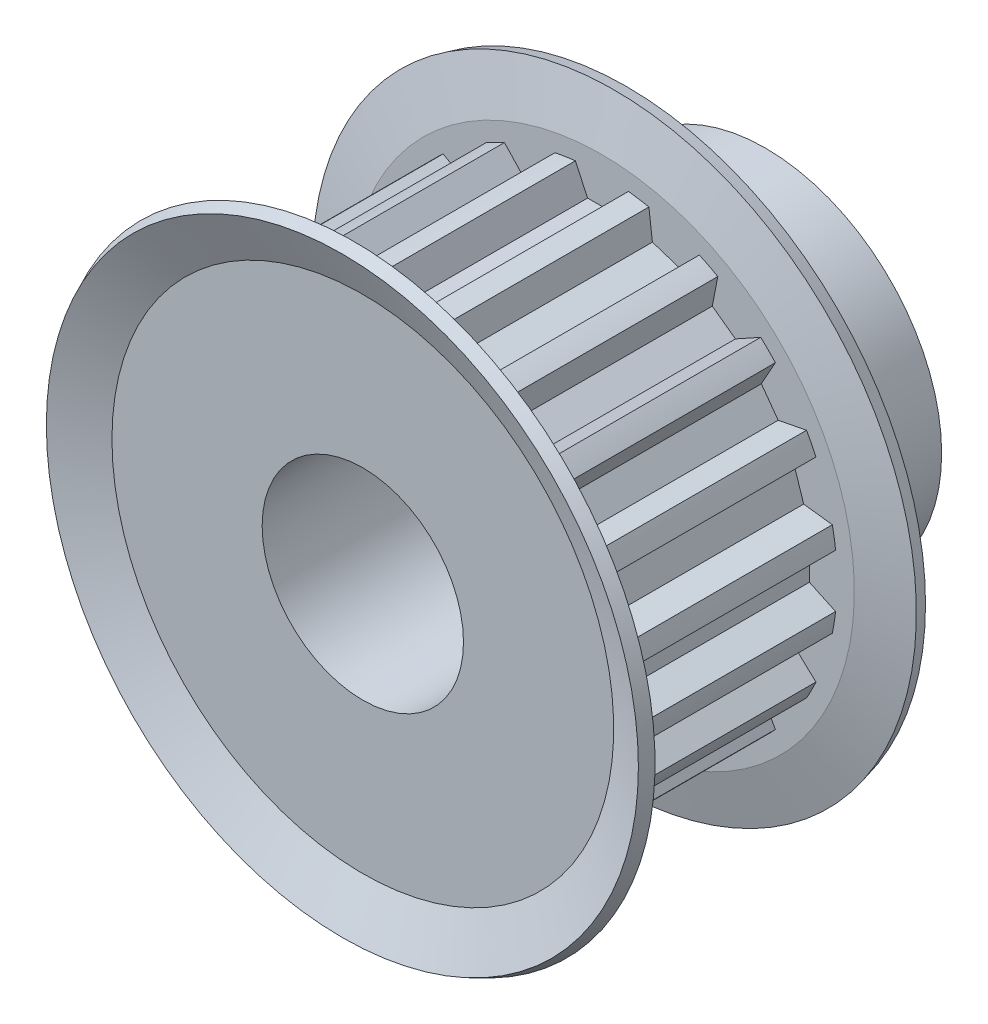
SolidWorks part; units mm, degrees
ref_plane "Plan de face" through (0, 0, 0) normal (0, 0, 1) x (1, 0, 0)
ref_plane "Plan de dessus" through (0, 0, 0) normal (0, 1, 0) x (1, 0, 0)
ref_plane "Plan de droite" through (0, 0, 0) normal (1, 0, 0) x (0, 0, -1)
sketch "Esquisse1" plane through (0, 0, 0) normal (0, 0, 1) x (1, 0, 0)
  circle A0 centre (0, 0) radius 9.345
  dimension "D1" = 18.69
extrude "Extrusion1" add sketch "Esquisse1" along normal blind 10
sketch "Esquisse2" plane through (0, 0, 10) normal (0, 0, 1) x (1, 0, 0)
  line L0 (-0.5685, 8.245) -> (0.5685, 8.245)
  line L1 (0.5685, 8.245) -> (1.2888, 9.7897)
  line L2 (1.2888, 9.7897) -> (-1.2888, 9.7897)
  line L3 (-1.2888, 9.7897) -> (-0.5685, 8.245)
  dimension "D1" = 8.245
  dimension "D2" = 1.137
  dimension "D3" = 0.5685
  dimension "D4" = 50
extrude "Extrusion2" cut sketch "Esquisse2" against normal through all
ref_axis "Axe1" through (0, 0, -0.6503) along (0, 0, 1)
pattern_circular "Répétition circulaire1" count 20 over 360 about axis through (0, 0, 0) along (0, 0, 1) of "Extrusion2"
sketch "Esquisse4" plane through (0, 0, 10) normal (0, 0, 1) x (1, 0, 0)
  circle A0 centre (0, 0) radius 4
extrude "Extrusion3" cut sketch "Esquisse4" against normal through all
sketch "Esquisse5" plane through (0, 0, 0) normal (1, 0, 0) x (0, 0, -1)
  line L0 (-10, 8) -> (-10, 9.969)
  line L1 (-10, 8.1314) -> (-10, 7.0045) construction
  line L2 (-10, 9.969) -> (-10.8125, 11.7626)
  line L3 (-10.8125, 11.7626) -> (-10.357, 11.9689)
  line L4 (-10.357, 11.9689) -> (-9.4792, 10.031)
  line L5 (-9.4792, 10.031) -> (-9.4792, 8)
  line L6 (-9.4792, 8) -> (-10, 8)
  line L7 (0, 8) -> (0, 9.969)
  line L8 (0, 8.1314) -> (0, 7.0045) construction
  line L9 (0, 9.969) -> (0.4809, 11.8784)
  line L10 (0.4809, 11.8784) -> (-0.0039, 12.0005)
  line L11 (-0.0039, 12.0005) -> (-0.5, 10.031)
  line L12 (-0.5, 10.031) -> (-0.5, 8)
  line L13 (-0.5, 8) -> (0, 8)
  line L14 (0.6503, 0) -> (-13.657, 0) construction
  line L16 (0, 7) -> (6, 7)
  line L17 (0, 7) -> (0, 4)
  line L18 (0, 4) -> (6, 4)
  line L19 (6, 7) -> (6, 4)
  dimension "D1" = 0
  dimension "D2" = 0.5208
  dimension "D3" = 0.5
  dimension "D4" = 0.5
  dimension "D5" = 0.5
  dimension "D6" = 8
  dimension "D7" = 8
  dimension "D8" = 1.969
  dimension "D9" = 2.031
  dimension "D10" = 1.969
  dimension "D11" = 2.031
  dimension "D12" = 1.969
  dimension "D13" = 1.969
  dimension "D14" = 6
  dimension "D15" = 4
  dimension "D16" = 7
revolve "Révolution1" add sketch "Esquisse5" angle 360 about axis through (0, 0, -0.6503) along (0, 0, 1)
